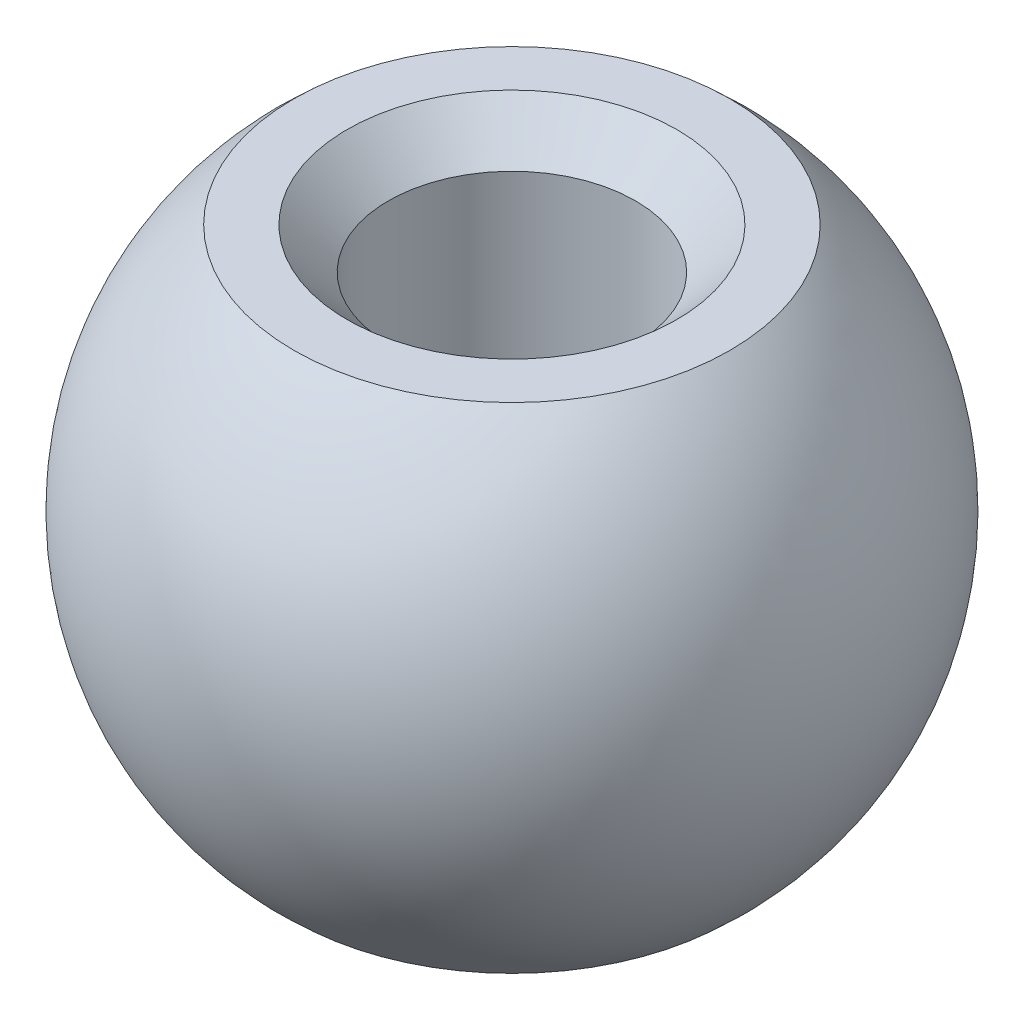
SolidWorks part; units mm, degrees
ref_plane "前视基准面" through (0, 0, 0) normal (0, 0, 1) x (1, 0, 0)
ref_plane "上视基准面" through (0, 0, 0) normal (0, 1, 0) x (1, 0, 0)
ref_plane "右视基准面" through (0, 0, 0) normal (1, 0, 0) x (0, 0, -1)
sketch "草图1" plane through (0, 0, 0) normal (0, 0, 1) x (1, 0, 0)
  line L0 (0, 4) -> (0, -4)
  arc A0 (0, -4) -> (0, 4) centre (0, 0) ccw
  dimension "D1" = 8
revolve "旋转1" add sketch "草图1" angle 360 about L0
sketch "草图2" plane through (0, 0, 0) normal (0, 0, 1) x (1, 0, 0)
  circle A0 centre (0, 0) radius 1.5
  dimension "D1" = 3
extrude "凸台-拉伸1" [suppressed] add sketch "草图2" along normal blind 20
sketch "草图3" plane through (0, 0, 0) normal (1, 0, 0) x (0, 0, -1)
  line L0 (0, 0) -> (3.5891, 0) construction
  line L1 (-2.6458, 3) -> (2.6458, 3)
  line L3 (-2.6458, -3) -> (2.6458, -3)
  circle A0 centre (0, 0) radius 4 construction
  arc A1 (-2.6458, -3) -> (2.6458, -3) centre (0, 0) ccw
  arc A2 (2.6458, 3) -> (-2.6458, 3) centre (0, 0) ccw
  dimension "D2" = 6
extrude "切除-拉伸1" cut sketch "草图3" against normal mid plane 10
sketch "草图4" plane through (0, -3, 0) normal (0, -1, 0) x (1, 0, 0)
  circle A0 centre (0, 0) radius 1.5
  dimension "D1" = 3
extrude "切除-拉伸2" cut sketch "草图4" against normal blind 10
chamfer "倒角1" distance 0.5 angle 45 2 edges at (0, 3, -1.5) (0, -3, -1.5)
